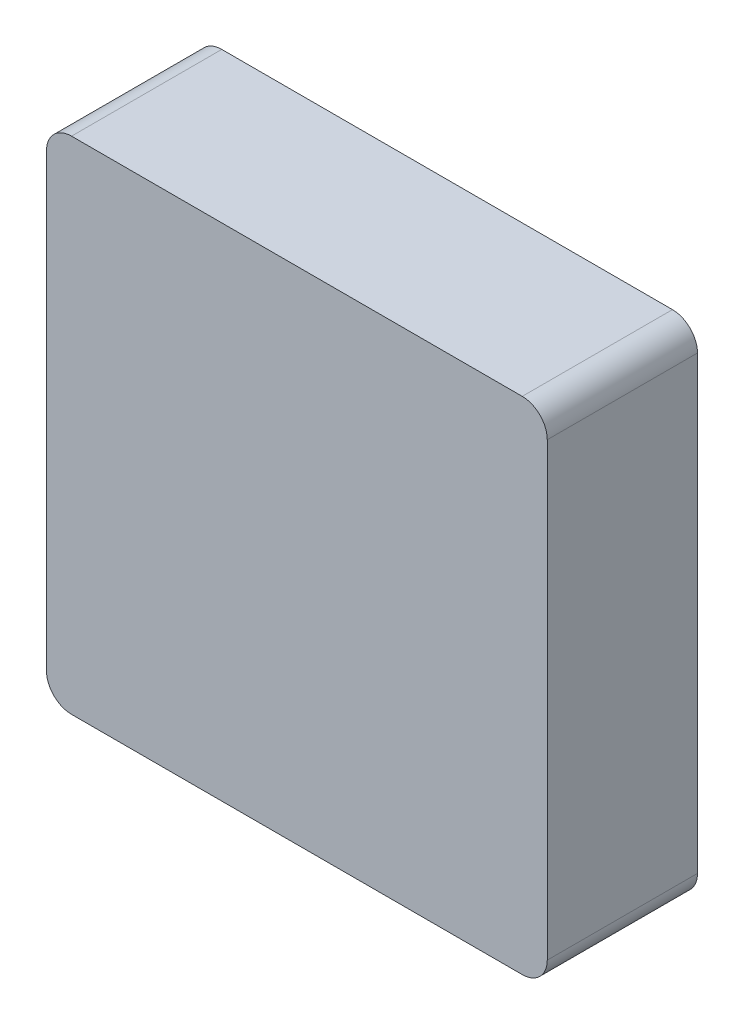
SolidWorks part; units mm, degrees
ref_plane "Front Plane" through (0, 0, 0) normal (0, 0, 1) x (1, 0, 0)
ref_plane "Top Plane" through (0, 0, 0) normal (0, 1, 0) x (1, 0, 0)
ref_plane "Right Plane" through (0, 0, 0) normal (1, 0, 0) x (0, 0, -1)
sketch "Sketch1" plane through (0, 0, 0) normal (0, 0, 1) x (1, 0, 0)
  line L1 (-45, -50) -> (45, -50)
  line L2 (-50, -45) -> (-50, 45)
  line L3 (-45, 50) -> (45, 50)
  line L4 (50, -45) -> (50, 45)
  line L5 (-50, -50) -> (50, 50) construction
  line L6 (-50, 50) -> (50, -50) construction
  arc A0 (-50, 45) -> (-45, 50) centre (-45, 45) cw
  arc A1 (-45, -50) -> (-50, -45) centre (-45, -45) cw
  arc A2 (45, -50) -> (50, -45) centre (45, -45) ccw
  arc A3 (50, 45) -> (45, 50) centre (45, 45) ccw
  point P0 (0, 0)
  dimension "D3" = 5
  dimension "D1" = 100
  dimension "D2" = 100
extrude "Boss-Extrude1" add sketch "Sketch1" along normal blind 30
